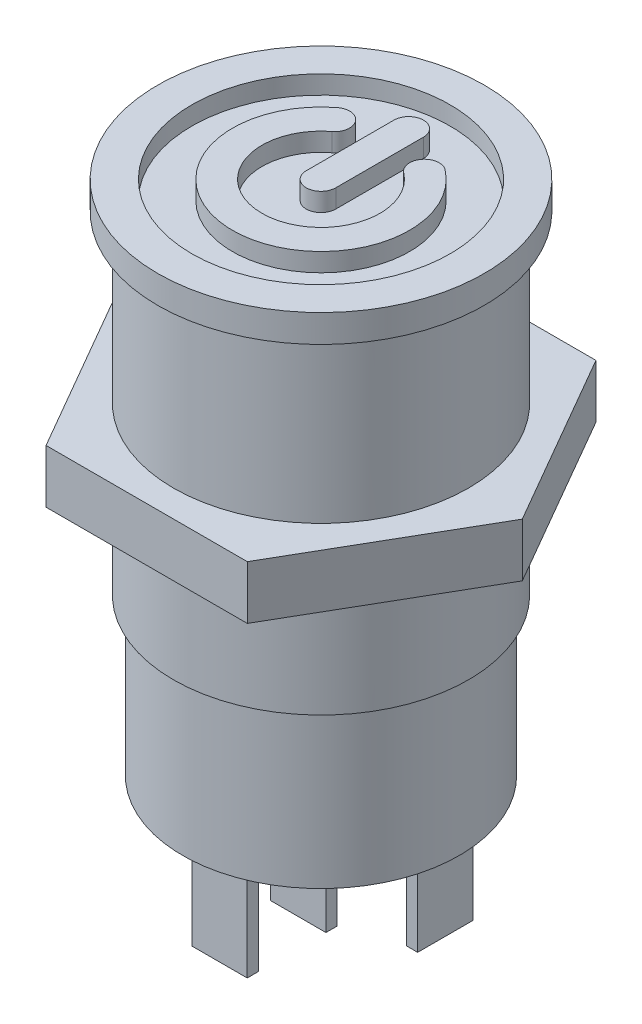
SolidWorks part; units mm, degrees
ref_plane "Plan de face" through (0, 0, 0) normal (0, 0, 1) x (1, 0, 0)
ref_plane "Plan de dessus" through (0, 0, 0) normal (0, 1, 0) x (1, 0, 0)
ref_plane "Plan de droite" through (0, 0, 0) normal (1, 0, 0) x (0, 0, -1)
sketch "Esquisse1" plane through (0, 0, 0) normal (0, 1, 0) x (1, 0, 0)
  circle A0 centre (0, 0) radius 8
  dimension "D1" = 16
extrude "Boss.-Extru.1" add sketch "Esquisse1" against normal blind 18
sketch "Esquisse2" plane through (0, 0, 0) normal (0, 1, 0) x (1, 0, 0)
  circle A0 centre (0, 0) radius 8.85
  dimension "D1" = 17.7
extrude "Boss.-Extru.2" add sketch "Esquisse2" along normal blind 1.5
sketch "Esquisse3" plane through (0, 1.5, 0) normal (0, 1, 0) x (1, 0, 0)
  line L0 (0, -4) -> (0, 0) construction
  line L1 (0, 0) -> (0, 4.7547) construction
  line L2 (-0.8, 0) -> (-0.8, 4.7547)
  line L3 (0.8, 0) -> (0.8, 4.7547)
  circle A0 centre (0, 0) radius 7
  arc A1 (-2.4276, 3.1791) -> (2.4276, 3.1791) centre (0, 0) ccw construction
  arc A2 (-2.9131, 3.815) -> (2.9131, 3.815) centre (0, 0) ccw
  arc A3 (-1.9421, 2.5433) -> (1.9421, 2.5433) centre (0, 0) ccw
  arc A4 (-1.9421, 2.5433) -> (-2.9131, 3.815) centre (-2.4276, 3.1791) ccw
  arc A5 (2.9131, 3.815) -> (1.9421, 2.5433) centre (2.4276, 3.1791) ccw
  arc A6 (-0.8, 0) -> (0.8, 0) centre (0, 0) ccw
  arc A7 (0.8, 4.7547) -> (-0.8, 4.7547) centre (0, 4.7547) ccw
  point P5 (0, -4)
  point P12 (0, 2.3773)
  dimension "D1" = 14
  dimension "D2" = 4
  dimension "D3" = 0.8
extrude "Enlèv. mat.-Extru.1" cut sketch "Esquisse3" against normal blind 1
sketch "Esquisse4" plane through (0, -18, 0) normal (0, -1, 0) x (1, 0, 0)
  circle A0 centre (0, 0) radius 7.5
  dimension "D1" = 15
extrude "Boss.-Extru.3" add sketch "Esquisse4" along normal blind 8.5
sketch "Esquisse5" plane through (0, -26.5, 0) normal (0, -1, 0) x (1, 0, 0)
  line L0 (0, 0) -> (0, 1.4764) construction
  line L1 (-4.9163, -0.3236) -> (-4.3163, -0.3236)
  line L2 (-4.9163, -0.3236) -> (-4.9163, -3.3236)
  line L3 (-4.9163, -3.3236) -> (-4.3163, -3.3236)
  line L4 (-4.3163, -0.3236) -> (-4.3163, -3.3236)
  line L5 (-1.5, 5.4997) -> (1.5, 5.4997)
  line L6 (-1.5, 5.4997) -> (-1.5, 4.8997)
  line L7 (-1.5, 4.8997) -> (1.5, 4.8997)
  line L8 (1.5, 5.4997) -> (1.5, 4.8997)
  line L9 (0, 0) -> (0.9286, 0) construction
  line L14 (4.3163, -0.3236) -> (4.3163, -3.3236)
  line L15 (4.9163, -3.3236) -> (4.3163, -3.3236)
  line L16 (4.9163, -0.3236) -> (4.9163, -3.3236)
  line L17 (4.9163, -0.3236) -> (4.3163, -0.3236)
  line L19 (-1.5, 1.2326) -> (1.5, 1.2326)
  line L20 (-1.5, 1.2326) -> (-1.5, 0.6326)
  line L21 (-1.5, 0.6326) -> (1.5, 0.6326)
  line L22 (1.5, 1.2326) -> (1.5, 0.6326)
  line L23 (-2, -5.3237) -> (1, -5.3237)
  line L24 (-2, -5.3237) -> (-2, -5.9237)
  line L25 (-2, -5.9237) -> (1, -5.9237)
  line L26 (1, -5.3237) -> (1, -5.9237)
  point P8 (0, 4.8997)
  point P22 (0, 0.6326)
  dimension "D1" = 0.6
  dimension "D2" = 3
extrude "Boss.-Extru.4" add sketch "Esquisse5" along normal blind 6
sketch "Esquisse6" plane through (0, 0, 0) normal (0, -1, 0) x (1, 0, 0)
  line L1 (10.9119, 0) -> (5.456, 9.45)
  line L2 (5.456, 9.45) -> (-5.456, 9.45)
  line L3 (-5.456, 9.45) -> (-10.9119, 0)
  line L4 (-10.9119, 0) -> (-5.456, -9.45)
  line L5 (-5.456, -9.45) -> (5.456, -9.45)
  line L6 (5.456, -9.45) -> (10.9119, 0)
  circle A0 centre (0, 0) radius 9.45 construction
  dimension "D1" = 18.9
extrude "Boss.-Extru.5" add sketch "Esquisse6" along normal blind 2.9 from offset 9
